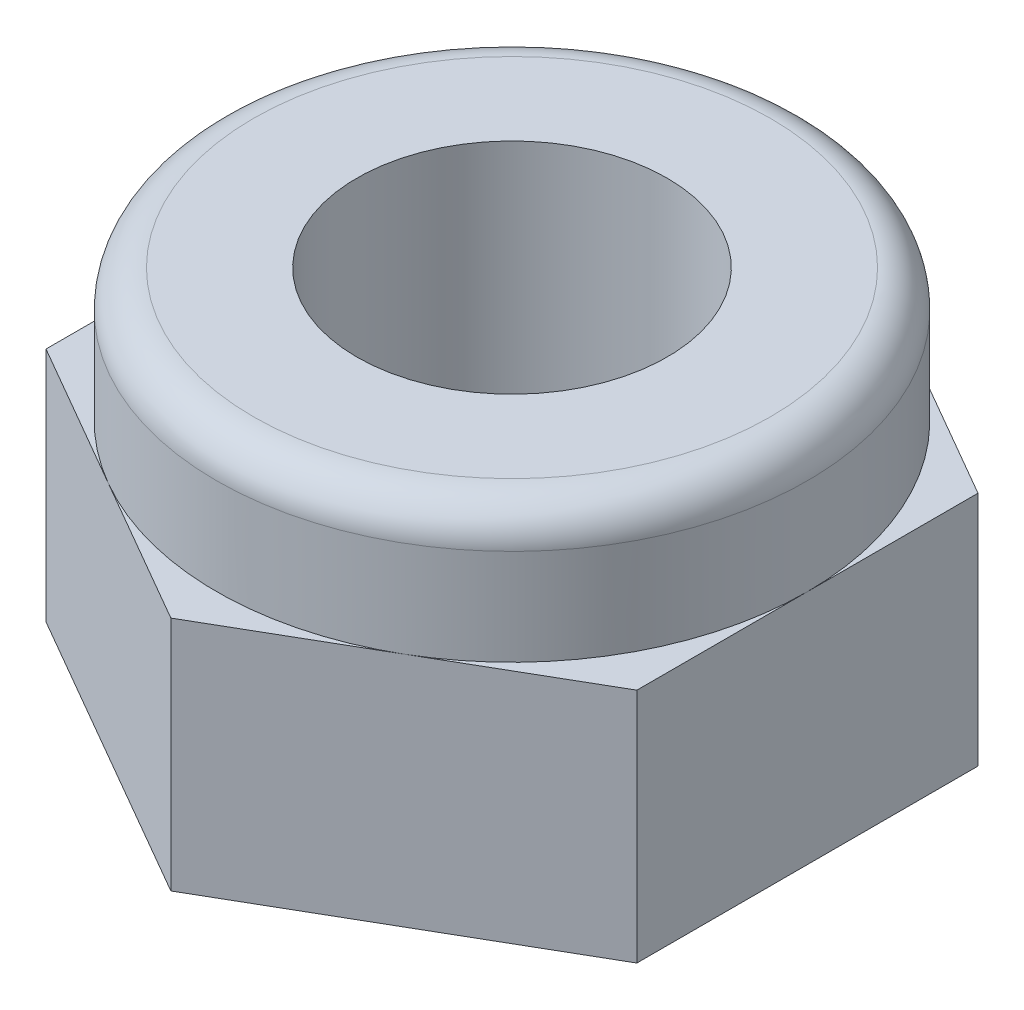
SolidWorks part; units mm, degrees
material "AISI 304"
ref_plane "前视基准面" through (0, 0, 0) normal (0, 0, 1) x (1, 0, 0)
ref_plane "上视基准面" through (0, 0, 0) normal (0, 1, 0) x (1, 0, 0)
ref_plane "右视基准面" through (0, 0, 0) normal (1, 0, 0) x (0, 0, -1)
sketch "草图1" plane through (0, 0, 0) normal (0, 1, 0) x (1, 0, 0)
  line L1 (0, 4.6188) -> (-4, 2.3094)
  line L2 (-4, 2.3094) -> (-4, -2.3094)
  line L3 (-4, -2.3094) -> (0, -4.6188)
  line L4 (0, -4.6188) -> (4, -2.3094)
  line L5 (4, -2.3094) -> (4, 2.3094)
  line L6 (4, 2.3094) -> (0, 4.6188)
  circle A0 centre (0, 0) radius 4 construction
  dimension "D1" = 8
extrude "凸台-拉伸1" add sketch "草图1" along normal blind 3.2
sketch "草图2" plane through (0, 3.2, 0) normal (0, 1, 0) x (1, 0, 0)
  circle A0 centre (0, 0) radius 4
extrude "凸台-拉伸2" add sketch "草图2" along normal blind 1.8
fillet "圆角1" radius 0.5 1 edges at (0, 5, 4)
hole_wizard "M5 螺纹孔1" positions "草图3" profile "草图4" tap size "M5" standard "GB" end condition through all
sketch "草图3" plane through (0, 5, 0) normal (0, 1, 0) x (1, 0, 0)
  point P0 (0, 0)
sketch "草图4" plane through (0, 5, 0) normal (1, 0, 0) x (0, 0, 1)
  line L0 (0, 0) -> (0, 5)
  line L1 (0, 5) -> (2.1, 5)
  line L2 (2.1, 5) -> (2.1, 0)
  line L5 (2.1, 0) -> (0, 0)
  line L11 (0, -6.35) -> (0, 107.95) construction
  dimension "通孔螺纹孔钻头直径" = 4.2
  dimension "通孔螺纹孔钻头深度" = 5
cosmetic thread "孔螺蚊线1" parameters "D2"=5
